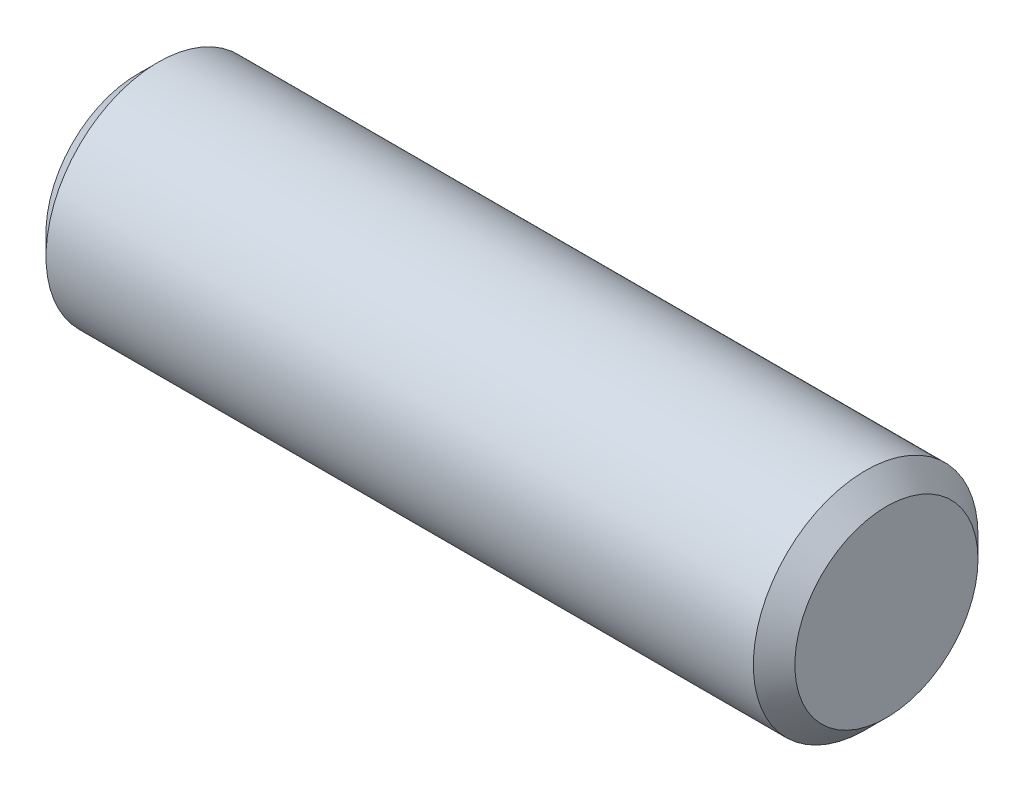
SolidWorks part; units mm, degrees
revolve "BaseBody" add sketch "BodySke" angle 360 about L14
sketch "BodySke" plane through (0, 0, 0) normal (0, 0, 1) x (1, 0, 0)
  line L0 (15.109, 15.875) -> (15.109, -6.35) construction
  line L1 (1, 15.875) -> (1, -3.175) construction
  line L2 (20, 6.35) -> (20, 3.175) construction
  line L10 (0, 3) -> (20, 3)
  line L12 (20, 3) -> (20, 0)
  line L13 (20, 0) -> (0, 0)
  line L14 (-3.175, 0) -> (107.95, 0) construction
  line L18 (0, 3) -> (0, 0)
  dimension "Diameter" = 6
  dimension "Length" = 20
  dimension "Advance" = 1
  dimension "Minor_dia" = 4.891
  dimension "Thread_max" = 20
cosmetic thread "ThreadCosmetic" parameters "Thread_minor"=4.891
ref_plane "Plane1" through (0, 0, 0) normal (0, 0, 1) x (1, 0, 0)
ref_plane "Plane2" through (0, 0, 0) normal (0, 1, 0) x (1, 0, 0)
ref_plane "Plane3" through (0, 0, 0) normal (1, 0, 0) x (0, 0, -1)
chamfer "Chamfer1" distance 0.5545 angle 45 2 edges at (0, 0, 3) (20, 0, 3)
sketch "ThdSchSke" plane through (0, 0, 0) normal (0, 0, 1) x (1, 0, 0)
  line L0 (0.3883, -2.4455) -> (0, -3)
  line L1 (0.3883, -2.4455) -> (0.7765, -3)
  line L2 (0.7765, -3) -> (0.7765, -3.75)
  line L3 (-3.175, 0) -> (5.1513, 0) construction
  line L4 (0, 3) -> (0, -3) construction
  line L5 (0.7765, -3.75) -> (0, -3.75)
  line L6 (0, -3.75) -> (0, -3)
  dimension "Thread_minor" = 4.891
  dimension "Diameter" = 6
revolve "ThreadSchematic" [suppressed] cut sketch "ThdSchSke" angle 360 about L3
pattern_linear "ThdSchPat" [suppressed]
equation "\"Thread_minor@ThreadCosmetic\" = \"Minor_dia@BodySke\""
equation "\"Chamfer@Chamfer1\" =  ( \"Diameter@BodySke\" - \"Minor_dia@BodySke\" ) / 2"
equation "\"Thread_minor@ThdSchSke\" = \"Minor_dia@BodySke\""
equation "\"Diameter@ThdSchSke\" = \"Diameter@BodySke\""
equation "\"Overcut@ThdSchSke\" = \"Diameter@BodySke\" * 1.25"
equation "\"Num_threads@ThdSchPat\" = int( (\"Thread_max@BodySke\" - \"Advance@BodySke\" ) / \"Advance@BodySke\" + 0.999 ) + 1"
equation "\"Advance@ThdSchPat\" = \"Thread_max@BodySke\" /  ( \"Num_threads@ThdSchPat\" - 1 ) 'relax it"
equation "\"Num_threads@ThdSchPat\" = \"Num_threads@ThdSchPat\" - sgn( \"Num_threads@ThdSchPat\" - 1 ) '---chamfered tips only---"
